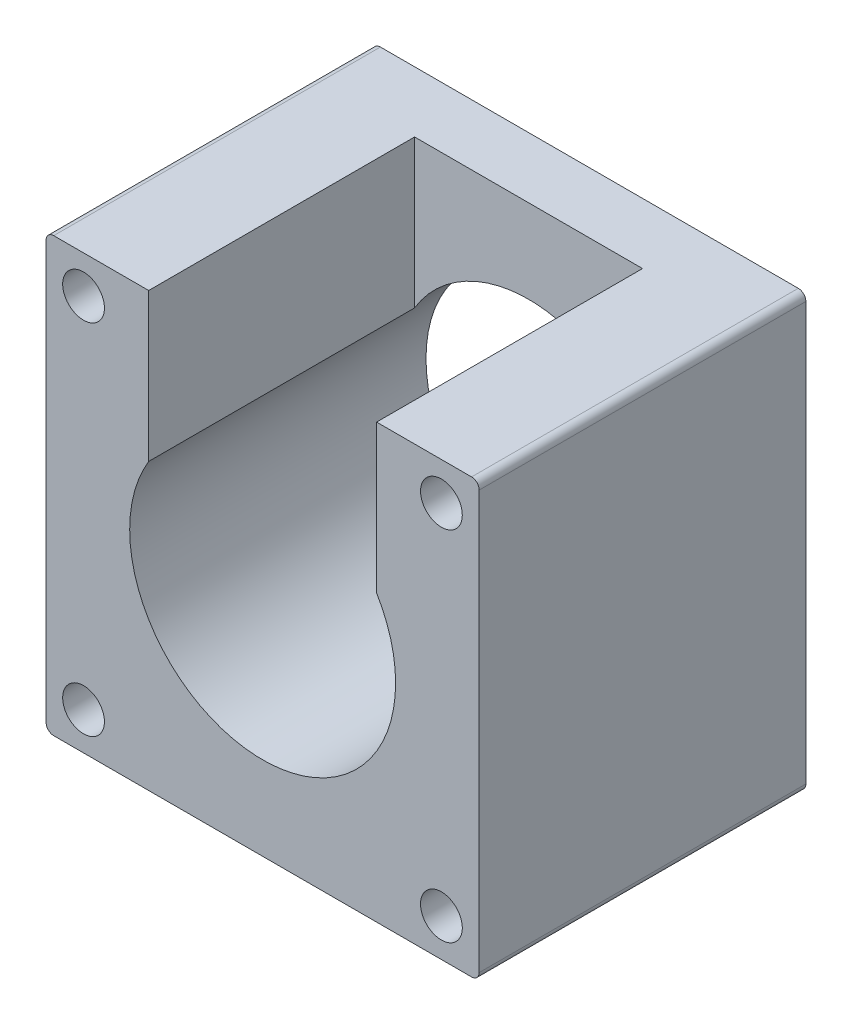
SolidWorks part; units mm, degrees
ref_plane "Plan de face" through (0, 0, 0) normal (0, 0, 1) x (1, 0, 0)
ref_plane "Plan de dessus" through (0, 0, 0) normal (0, 1, 0) x (1, 0, 0)
ref_plane "Plan de droite" through (0, 0, 0) normal (1, 0, 0) x (0, 0, -1)
sketch "Esquisse1" plane through (0, 0, 0) normal (0, 0, 1) x (1, 0, 0)
  line L0 (0, 0) -> (57, 57) construction
  line L1 (1, 0) -> (56, 0)
  line L2 (0, 1) -> (0, 56)
  line L3 (1, 57) -> (56, 57)
  line L4 (57, 1) -> (57, 56)
  line L5 (0, 57) -> (57, 0) construction
  line L6 (28.5, 28.5) -> (66.6579, 28.5) construction
  circle A0 centre (28.5, 28.5) radius 17.5
  circle A1 centre (4.9267, 52.0733) radius 2.75
  circle A2 centre (52.0266, 52.0266) radius 2.75
  circle A3 centre (4.9267, 4.9267) radius 2.75
  circle A4 centre (52.0266, 4.9734) radius 2.75
  arc A5 (56, 0) -> (57, 1) centre (56, 1) ccw
  arc A6 (1, 0) -> (0, 1) centre (1, 1) cw
  arc A7 (0, 56) -> (1, 57) centre (1, 56) cw
  arc A8 (56, 57) -> (57, 56) centre (56, 56) cw
  dimension "D3" = 35
  dimension "D5" = 5.5
  dimension "D6" = 5.5
  dimension "D7" = 1
  dimension "D1" = 57
  dimension "D2" = 57
  dimension "D4" = 47.1
extrude "Boss.-Extru.1" add sketch "Esquisse1" along normal blind 43
sketch "Esquisse2" plane through (0, 57, 0) normal (0, 1, 0) x (1, 0, 0)
  line L0 (28.5, 0) -> (28.5, -45.0121) construction
  line L1 (56, 0) -> (1, 0) construction
  line L2 (56, -43) -> (1, -43) construction
  line L3 (13.5, -43) -> (43.5, -43)
  line L4 (13.5, -43) -> (13.5, -8)
  line L5 (13.5, -8) -> (43.5, -8)
  line L6 (43.5, -43) -> (43.5, -8)
  dimension "D1" = 35
  dimension "D2" = 30
  dimension "D3" = 15
extrude "Enlèv. mat.-Extru.1" cut sketch "Esquisse2" against normal blind 30
sketch "Esquisse3" plane through (0, 0, 0) normal (0, 0, -1) x (-1, 0, 0)
  circle A0 centre (-28.5, 28.5) radius 22.5
extrude "Enlèv. mat.-Extru.2" cut sketch "Esquisse3" against normal blind 4
